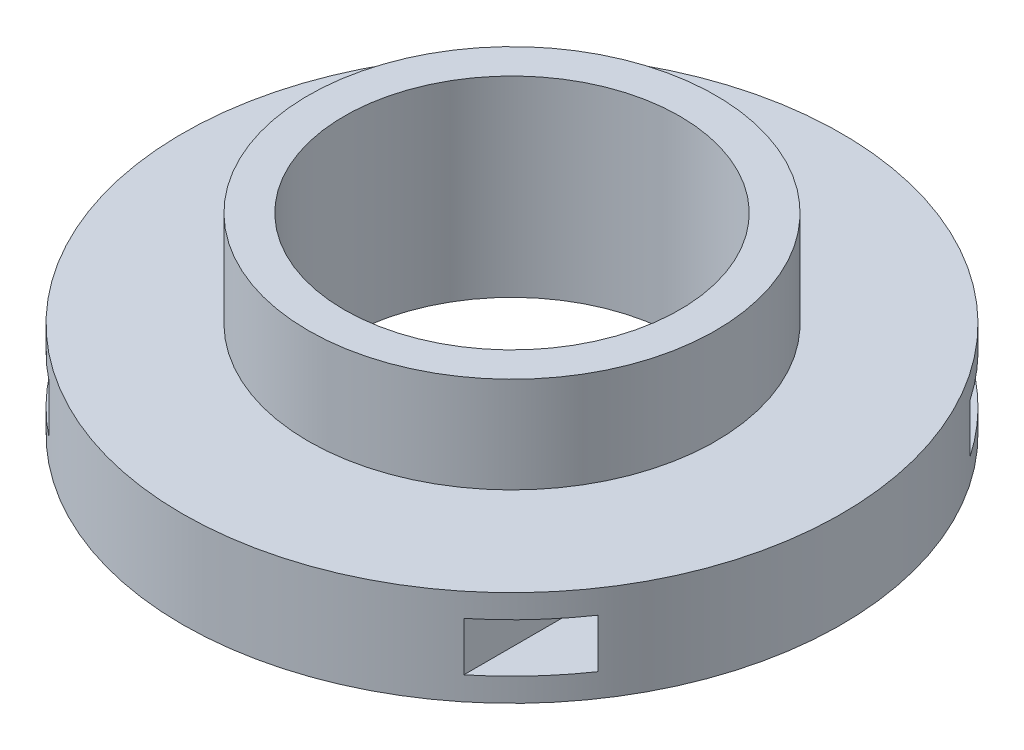
SolidWorks part; units mm, degrees
ref_plane "Front Plane" through (0, 0, 0) normal (0, 0, 1) x (1, 0, 0)
ref_plane "Top Plane" through (0, 0, 0) normal (0, 1, 0) x (1, 0, 0)
ref_plane "Right Plane" through (0, 0, 0) normal (1, 0, 0) x (0, 0, -1)
sketch "Sketch1" plane through (0, 0, 0) normal (0, 1, 0) x (1, 0, 0)
  circle A0 centre (0, 0) radius 13.75
  dimension "D1" = 27.5
extrude "Boss-Extrude1" add sketch "Sketch1" along normal blind 4 contours A0
sketch "Sketch5" plane through (0, 0, 0) normal (0, 1, 0) x (1, 0, 0)
  circle A0 centre (0, 0) radius 8.5
  dimension "D1" = 17
extrude "Boss-Extrude2" add sketch "Sketch5" along normal blind 4 from surface at 4 starting at face at (0, 4, 13.75)
ref_plane "Plane2" through (0, 2, 0) normal (0, 1, 0) x (1, 0, 0)
sketch "Sketch6" plane through (0, 0, 0) normal (0, 0, 1) x (1, 0, 0)
  line L0 (15.125, 2) -> (-15.125, 2) construction
  line L1 (-11.4, 0.9801) -> (-8.5113, 0.9801)
  line L2 (-11.4, 0.9801) -> (-11.4, 3.0199)
  line L3 (-11.4, 3.0199) -> (-8.5113, 3.0199)
  line L4 (-8.5113, 0.9801) -> (-8.5113, 3.0199)
  line L5 (-11.4, 0.9801) -> (-8.5113, 3.0199) construction
  line L6 (-11.4, 3.0199) -> (-8.5113, 0.9801) construction
  line L8 (11.3484, 0.9801) -> (8.666, 0.9801)
  line L9 (11.3484, 0.9801) -> (11.3484, 3.0199)
  line L10 (11.3484, 3.0199) -> (8.666, 3.0199)
  line L11 (8.666, 0.9801) -> (8.666, 3.0199)
  line L12 (11.3484, 0.9801) -> (8.666, 3.0199) construction
  line L13 (11.3484, 3.0199) -> (8.666, 0.9801) construction
  point P0 (-9.9556, 2)
  point P7 (10.0072, 2)
extrude "Cut-Extrude1" cut sketch "Sketch6" against normal through all and the other way through all
sketch "Sketch8" plane through (0, 0, 0) normal (0, 1, 0) x (1, 0, 0)
  circle A0 centre (0, 0) radius 7
  dimension "D1" = 14
extrude "Cut-Extrude3" cut sketch "Sketch8" along normal blind 12
